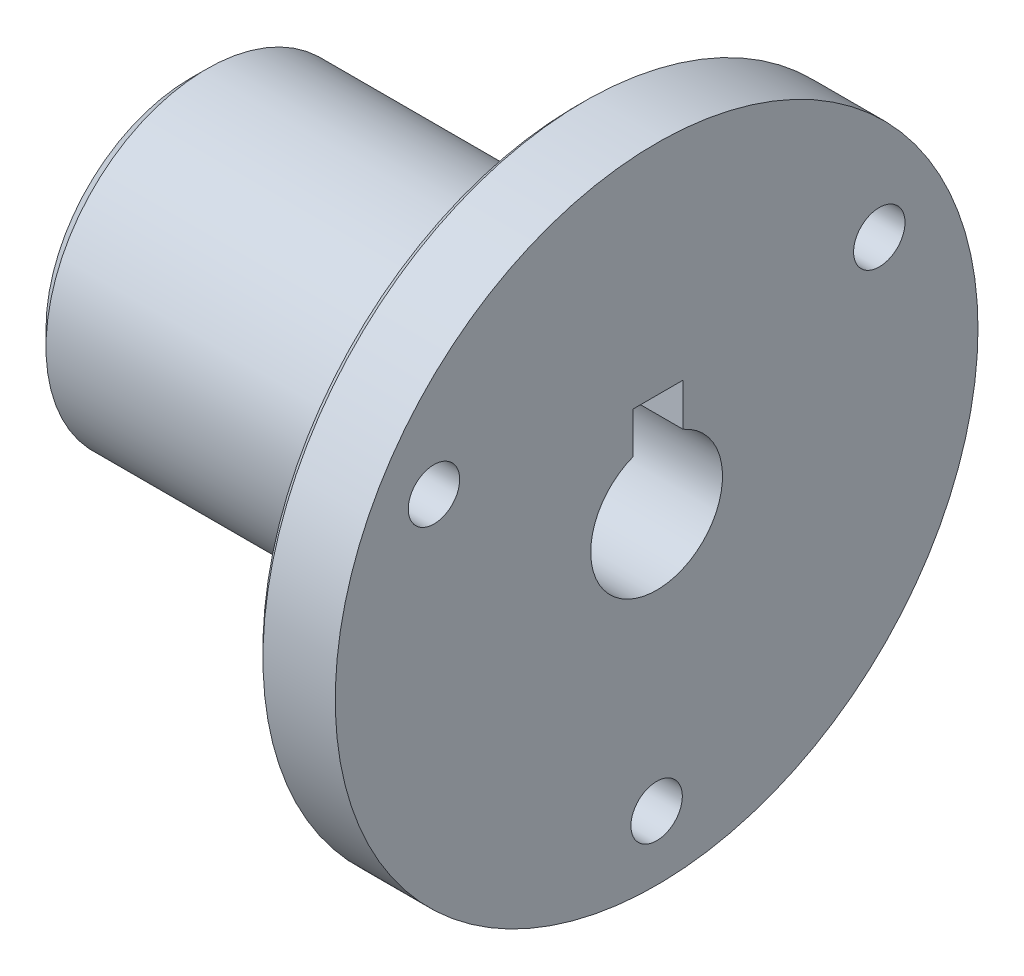
SolidWorks part; units mm, degrees
ref_plane "Front" through (0, 0, 0) normal (0, 0, 1) x (1, 0, 0)
ref_plane "Top" through (0, 0, 0) normal (0, 1, 0) x (1, 0, 0)
ref_plane "Right" through (0, 0, 0) normal (1, 0, 0) x (0, 0, -1)
sketch "草图1" plane through (0, 0, 0) normal (1, 0, 0) x (0, 0, -1)
  line L0 (-1.46, 6.0088) -> (-1.46, 6.4)
  line L1 (-0.0142, 6.0088) -> (-1.46, 6.0088) construction
  line L2 (-1.46, 6.0088) -> (-1.46, 3.8312)
  line L3 (-0.0142, 6.0088) -> (1.64, 6.0088) construction
  line L4 (1.64, 6.0088) -> (1.64, 3.7577)
  line L5 (-1.46, 6.4) -> (1.64, 6.4)
  line L6 (1.64, 6.4) -> (1.64, 6.0088)
  arc A0 (-1.46, 3.8312) -> (1.64, 3.7577) centre (0, 0) ccw
  circle A1 centre (0, 0) radius 10
  dimension "D1" = 4.1
  dimension "D2" = 20
  dimension "D3" = 6.4
  dimension "D4" = 3.1
extrude "凸台-拉伸1" add sketch "草图1" along normal blind 24
sketch "草图2" plane through (24, 0, 0) normal (1, 0, 0) x (0, 0, -1)
  line L0 (0, 0) -> (13.8564, 8) construction
  line L1 (0, 0) -> (-13.8564, 8) construction
  line L2 (0, 0) -> (0, -16) construction
  circle A0 centre (0, 0) radius 16 construction
  circle A1 centre (0, 0) radius 20
  circle A2 centre (-13.8564, 8) radius 1.6
  circle A3 centre (13.8564, 8) radius 1.6
  circle A4 centre (0, -16) radius 1.6
extrude "凸台-拉伸2" add sketch "草图2" along normal blind 5
sketch "草图5" plane through (29, 0, 0) normal (1, 0, 0) x (0, 0, -1)
  line L0 (-1.46, 6.4) -> (-1.46, 3.8312)
  line L1 (-1.46, 6.4) -> (1.64, 6.4)
  line L2 (1.64, 6.4) -> (1.64, 3.7577)
  arc A0 (-1.46, 3.8312) -> (1.64, 3.7577) centre (0, 0) ccw
extrude "切除-拉伸1" cut sketch "草图5" against normal up to next
chamfer "倒角1" distance 0.5 angle 45 1 edges at (0, -4.0988, 0.0972)
chamfer "倒角2" distance 1 angle 45 1 edges at (0, 0, -10)
chamfer "倒角3" distance 0.5 angle 45 1 edges at (24, 0, -20)
chamfer "倒角4" distance 2 angle 45 1 edges at (24, 0, -10)
